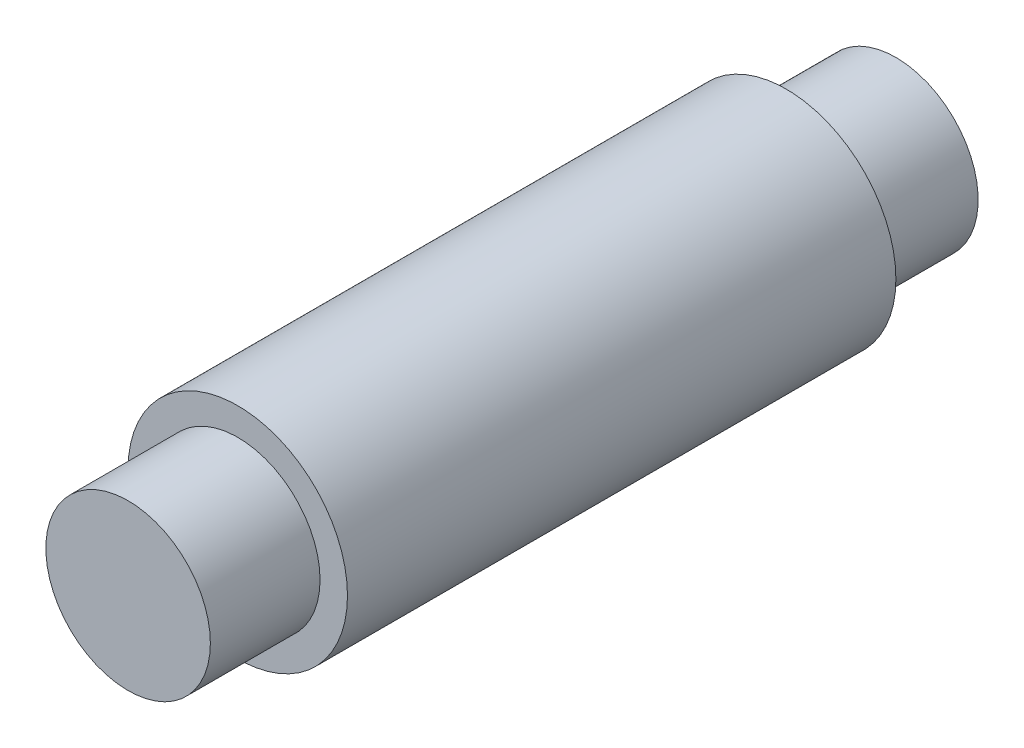
SolidWorks part; units mm, degrees
ref_plane "Front Plane" through (0, 0, 0) normal (0, 0, 1) x (1, 0, 0)
ref_plane "Top Plane" through (0, 0, 0) normal (0, 1, 0) x (1, 0, 0)
ref_plane "Right Plane" through (0, 0, 0) normal (1, 0, 0) x (0, 0, -1)
sketch "Sketch1" plane through (0, 0, 0) normal (0, 0, 1) x (1, 0, 0)
  circle A0 centre (0, 0) radius 12.7
  dimension "D1" = 25.4
extrude "Boss-Extrude1" add sketch "Sketch1" against normal blind 88.9 from offset 44.45
sketch "Sketch2" plane through (0, 0, 44.45) normal (0, 0, 1) x (1, 0, 0)
  circle A0 centre (0, 0) radius 12.7
  circle A1 centre (0, 0) radius 9.525
extrude "Cut-Extrude1" cut sketch "Sketch2" against normal blind 12.7
sketch "Sketch3" plane through (0, 0, -44.45) normal (0, 0, -1) x (-1, 0, 0)
  circle A0 centre (0, 0) radius 12.7
  circle A1 centre (0, 0) radius 9.525
extrude "Cut-Extrude2" cut sketch "Sketch3" against normal blind 12.7
